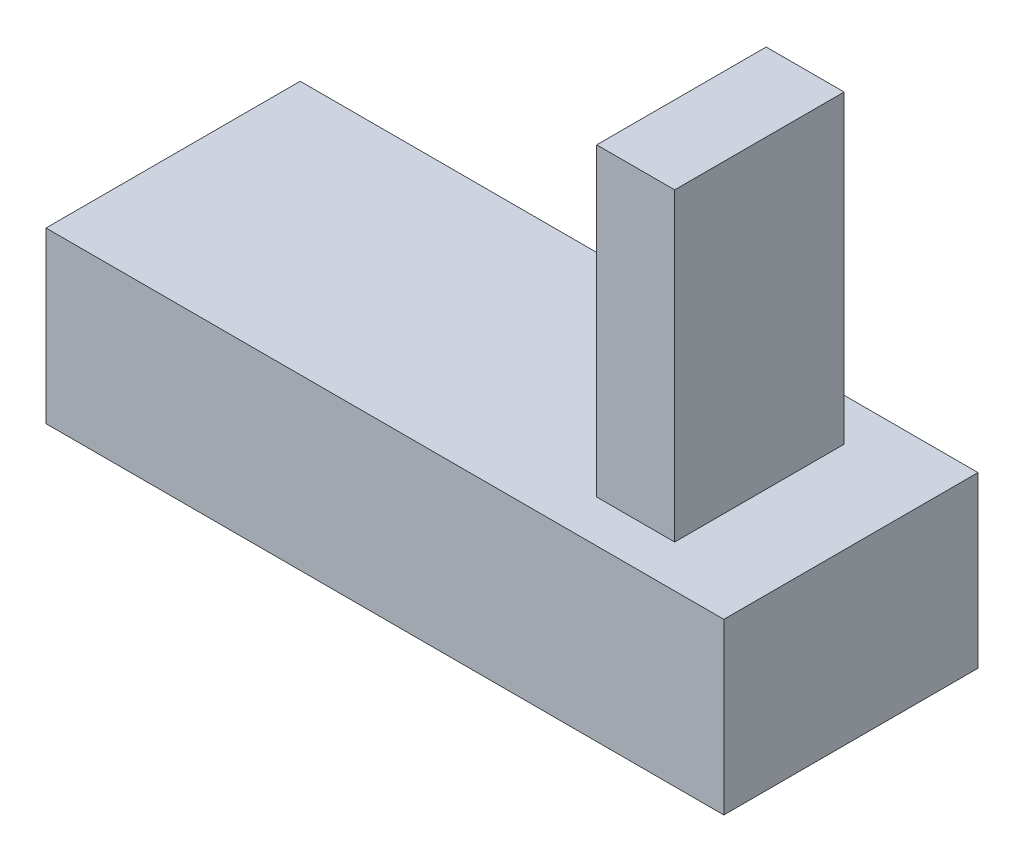
SolidWorks part; units mm, degrees
ref_plane "Спереди" through (0, 0, 0) normal (0, 0, 1) x (1, 0, 0)
ref_plane "Сверху" through (0, 0, 0) normal (0, 1, 0) x (1, 0, 0)
ref_plane "Справа" through (0, 0, 0) normal (1, 0, 0) x (0, 0, -1)
sketch "Sketch1" plane through (0, 0, 0) normal (0, 1, 0) x (1, 0, 0)
  line L1 (-20, -7.5) -> (20, -7.5)
  line L2 (-20, -7.5) -> (-20, 7.5)
  line L3 (-20, 7.5) -> (20, 7.5)
  line L4 (20, -7.5) -> (20, 7.5)
  line L5 (-20, -7.5) -> (20, 7.5) construction
  line L6 (-20, 7.5) -> (20, -7.5) construction
  point P0 (0, 0)
  dimension "D1" = 15
  dimension "D2" = 40
extrude "Boss-Extrude1" add sketch "Sketch1" along normal blind 10 contours L3 L4 L1 L2
sketch "Sketch2" plane through (0, 10, 0) normal (0, 1, 0) x (1, 0, 0)
  line L0 (-20, -7.5) -> (-20, 7.5) construction
  line L1 (10, -5) -> (14.6, -5)
  line L2 (10, -5) -> (10, 5)
  line L3 (10, 5) -> (14.6, 5)
  line L4 (14.6, -5) -> (14.6, 5)
  line L5 (10, -5) -> (14.6, 5) construction
  line L6 (10, 5) -> (14.6, -5) construction
  point P0 (12.3, 0)
  dimension "D1" = 10
  dimension "D2" = 4.6
  dimension "D3" = 30
extrude "Boss-Extrude2" add sketch "Sketch2" along normal blind 18
